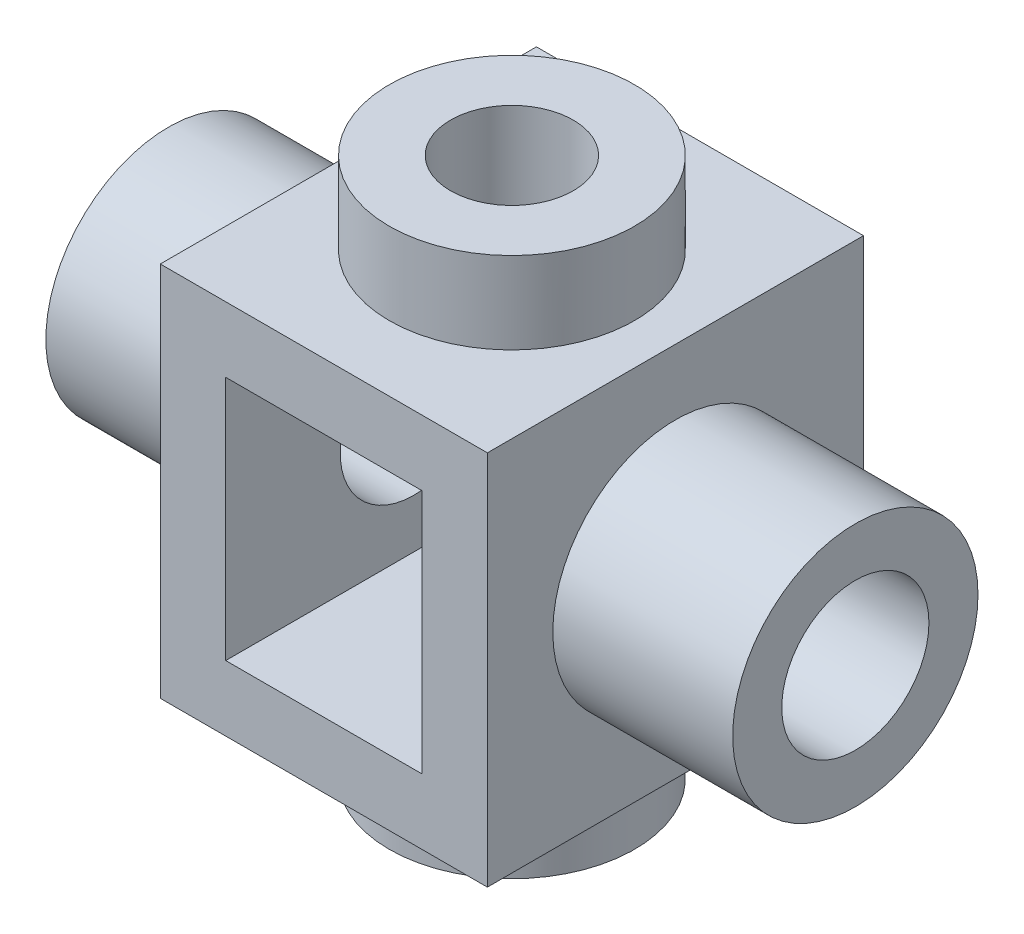
SolidWorks part; units mm, degrees
ref_plane "Front Plane" through (0, 0, 0) normal (0, 0, 1) x (1, 0, 0)
ref_plane "Top Plane" through (0, 0, 0) normal (0, 1, 0) x (1, 0, 0)
ref_plane "Right Plane" through (0, 0, 0) normal (1, 0, 0) x (0, 0, -1)
sketch "Sketch1" plane through (0, 0, 0) normal (0, 0, 1) x (1, 0, 0)
  line L0 (0, 0) -> (0, 43034.858) construction
  line L1 (0, 0) -> (43034.858, 0) construction
  line L3 (0, 0) -> (40, 0)
  line L4 (0, 0) -> (0, 46)
  line L5 (0, 46) -> (40, 46)
  line L6 (40, 0) -> (40, 46)
  dimension "D1" = 46
  dimension "D2" = 40
extrude "Boss-Extrude1" add sketch "Sketch1" along normal blind 46
sketch "Sketch2" plane through (0, 46, 0) normal (0, 1, 0) x (1, 0, 0)
  line L0 (40, -46) -> (0, -46) construction
  line L1 (0, -46) -> (0, 0) construction
  circle A0 centre (20, -23) radius 7.5
  circle A1 centre (20, -23) radius 15
  dimension "D1" = 15
  dimension "D2" = 30
  dimension "D3" = 23
  dimension "D4" = 20
extrude "Boss-Extrude2" add sketch "Sketch2" along normal blind 10 and the other way blind 56
sketch "Sketch3" plane through (40, 0, 0) normal (1, 0, 0) x (0, 0, -1)
  line L0 (-38, 0) -> (-8, 0) construction
  line L1 (0, 0) -> (0, 46) construction
  circle A0 centre (-23, 23) radius 9
  circle A1 centre (-23, 23) radius 15
  dimension "D1" = 18
  dimension "D2" = 30
  dimension "D3" = 23
  dimension "D4" = 23
extrude "Boss-Extrude3" add sketch "Sketch3" along normal blind 22 and the other way blind 62
sketch "Sketch4" plane through (40, 0, 0) normal (1, 0, 0) x (0, 0, -1)
  circle A0 centre (-23, 23) radius 9
  dimension "D1" = 18
extrude "Cut-Extrude1" cut sketch "Sketch4" against normal blind 130
sketch "Sketch5" plane through (0, 46, 0) normal (0, 1, 0) x (1, 0, 0)
  circle A0 centre (20, -23) radius 7.5
  dimension "D1" = 15
extrude "Cut-Extrude2" cut sketch "Sketch5" against normal blind 130
sketch "Sketch6" plane through (0, 0, 46) normal (0, 0, 1) x (1, 0, 0)
  line L0 (0, 0) -> (40, 0) construction
  line L1 (8, 8) -> (32, 8)
  line L2 (8, 8) -> (8, 38)
  line L3 (8, 38) -> (32, 38)
  line L4 (32, 8) -> (32, 38)
  line L5 (8, 8) -> (32, 38) construction
  line L6 (8, 38) -> (32, 8) construction
  line L7 (0, 38) -> (0, 8) construction
  point P0 (20, 23)
  dimension "D1" = 23
  dimension "D2" = 20
  dimension "D3" = 24
  dimension "D4" = 30
extrude "Cut-Extrude3" cut sketch "Sketch6" against normal blind 130
